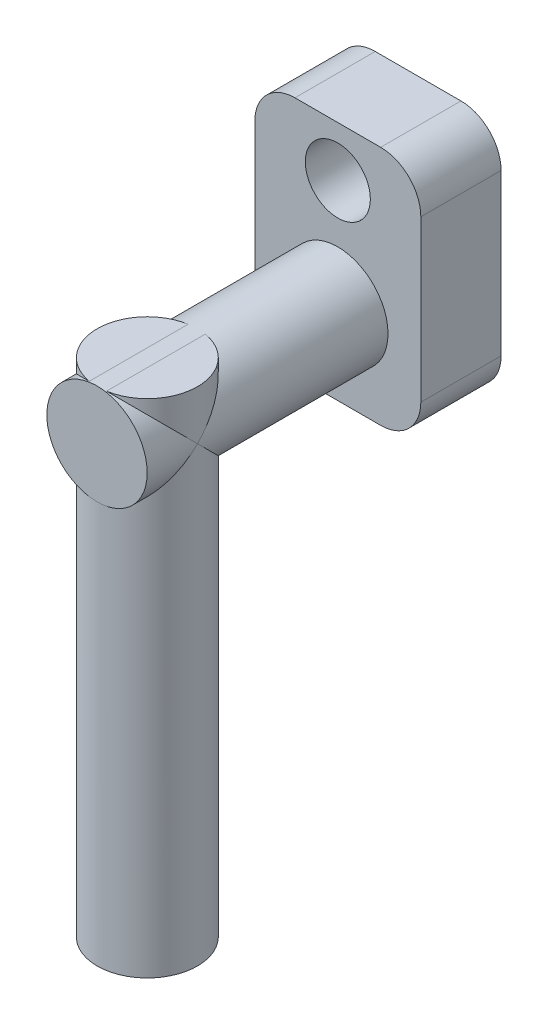
SolidWorks part; units mm, degrees
ref_plane "Piano frontale" through (0, 0, 0) normal (0, 0, 1) x (1, 0, 0)
ref_plane "Piano superiore" through (0, 0, 0) normal (0, 1, 0) x (1, 0, 0)
ref_plane "Piano destro" through (0, 0, 0) normal (1, 0, 0) x (0, 0, -1)
sketch "Schizzo1" plane through (0, 0, 0) normal (0, 0, 1) x (1, 0, 0)
  line L1 (-4.135, 6) -> (4.135, 6)
  line L2 (-4.135, 6) -> (-4.135, -6)
  line L3 (-4.135, -6) -> (4.135, -6)
  line L4 (4.135, 6) -> (4.135, -6)
  line L5 (-4.135, 6) -> (4.135, -6) construction
  line L6 (-4.135, -6) -> (4.135, 6) construction
  point P0 (0, 0)
  dimension "D1" = 8.27
  dimension "D2" = 12
extrude "Estrusione-Estrusione1" add sketch "Schizzo1" along normal blind 4
fillet "Raccordo1" radius 2 1 edges at (4.135, 6, 2)
fillet "Raccordo2" radius 2 3 edges at (-4.135, -6, 2) (4.135, -6, 2) (-4.135, 6, 2)
sketch "Schizzo3" plane through (0, 0, 4) normal (0, 0, 1) x (1, 0, 0)
  line L0 (2.135, 6) -> (-2.135, 6) construction
  line L1 (0, 3.5) -> (0, -1.8631) construction
  circle A0 centre (0, 3.5) radius 1.62
  circle A1 centre (0, -1.8631) radius 2.5
  dimension "D1" = 3.24
  dimension "D2" = 2.5
extrude "Taglio-Estrusione1" cut sketch "Schizzo3" against normal blind 4 contours A0
sketch "Schizzo4" plane through (0, 0, 4) normal (0, 0, 1) x (1, 0, 0)
  circle A0 centre (0, -1.8631) radius 2.5
  dimension "D1" = 5
extrude "Estrusione-Estrusione2" add sketch "Schizzo4" along normal blind 12
ref_plane "Piano1" through (0, 0.6, 0) normal (0, 1, 0) x (1, 0, 0)
sketch "Schizzo5" plane through (0, 0.6, 0) normal (0, 1, 0) x (1, 0, 0)
  circle A0 centre (0, -13.4916) radius 2.5
extrude "Estrusione-Estrusione3" add sketch "Schizzo5" against normal blind 25
